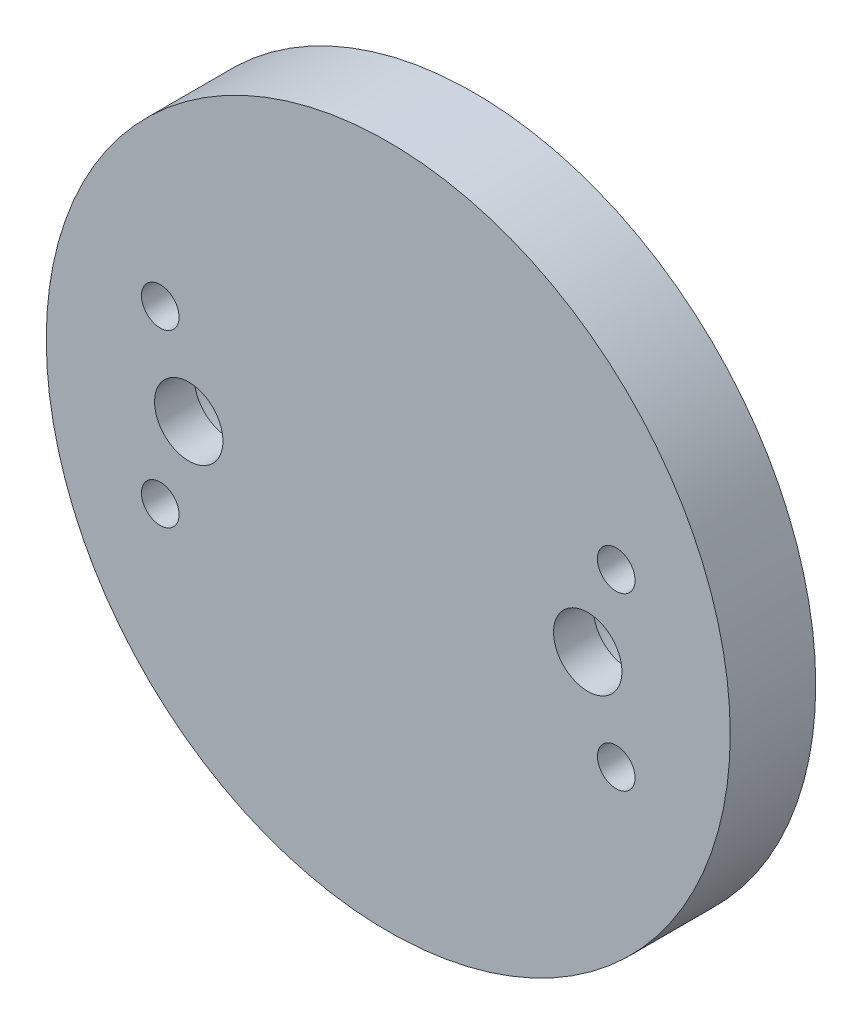
SolidWorks part; units mm, degrees
ref_plane "前视基准面" through (0, 0, 0) normal (0, 0, 1) x (1, 0, 0)
ref_plane "上视基准面" through (0, 0, 0) normal (0, 1, 0) x (1, 0, 0)
ref_plane "右视基准面" through (0, 0, 0) normal (1, 0, 0) x (0, 0, -1)
sketch "草图1" plane through (0, 0, 0) normal (0, 0, 1) x (1, 0, 0)
  circle A0 centre (0, 0) radius 60
  point P0 (0, 0)
  dimension "D1" = 120
extrude "凸台-拉伸1" add sketch "草图1" along normal blind 15
sketch "草图2" plane through (0, 0, 0) normal (0, 0, -1) x (-1, 0, 0)
  line L0 (-60, 0) -> (60, 0) construction
  line L4 (0, 60) -> (0, -60) construction
  circle A0 centre (-35, 0) radius 6
  circle A1 centre (35, 0) radius 6
  circle A2 centre (0, 0) radius 60 construction
  dimension "D2" = 12
  dimension "D3" = 70
extrude "切除-拉伸1" cut sketch "草图2" against normal through all
sketch "草图3" plane through (0, 0, 0) normal (0, 0, -1) x (-1, 0, 0)
  line L0 (0, 0) -> (35, 0) construction
  circle A1 centre (35, 0) radius 11
  circle A5 centre (-35, 0) radius 11
  dimension "D1" = 35
  dimension "D2" = 22
  dimension "D4" = 70
extrude "切除-拉伸2" cut sketch "草图3" against normal blind 8
sketch "草图5" plane through (0, 0, 15) normal (0, 0, 1) x (1, 0, 0)
  line L1 (40, 15) -> (-40, 15) construction
  line L2 (40, 15) -> (40, -15) construction
  line L3 (40, -15) -> (-40, -15) construction
  line L4 (-40, 15) -> (-40, -15) construction
  line L5 (40, 15) -> (-40, -15) construction
  line L6 (40, -15) -> (-40, 15) construction
  circle A0 centre (40, 15) radius 3.3
  circle A1 centre (40, -15) radius 3.3
  circle A2 centre (-40, -15) radius 3.3
  circle A3 centre (-40, 15) radius 3.3
  point P0 (0, 0)
  dimension "D3" = 6.6
  dimension "D1" = 30
  dimension "D2" = 80
extrude "切除-拉伸4" cut sketch "草图5" against normal blind 10
sketch "草图6" plane through (0, 0, 0) normal (0, 0, -1) x (-1, 0, 0)
  circle A0 centre (35, 0) radius 14
  circle A1 centre (-35, 0) radius 14
extrude "切除-拉伸5" cut sketch "草图6" against normal blind 7
